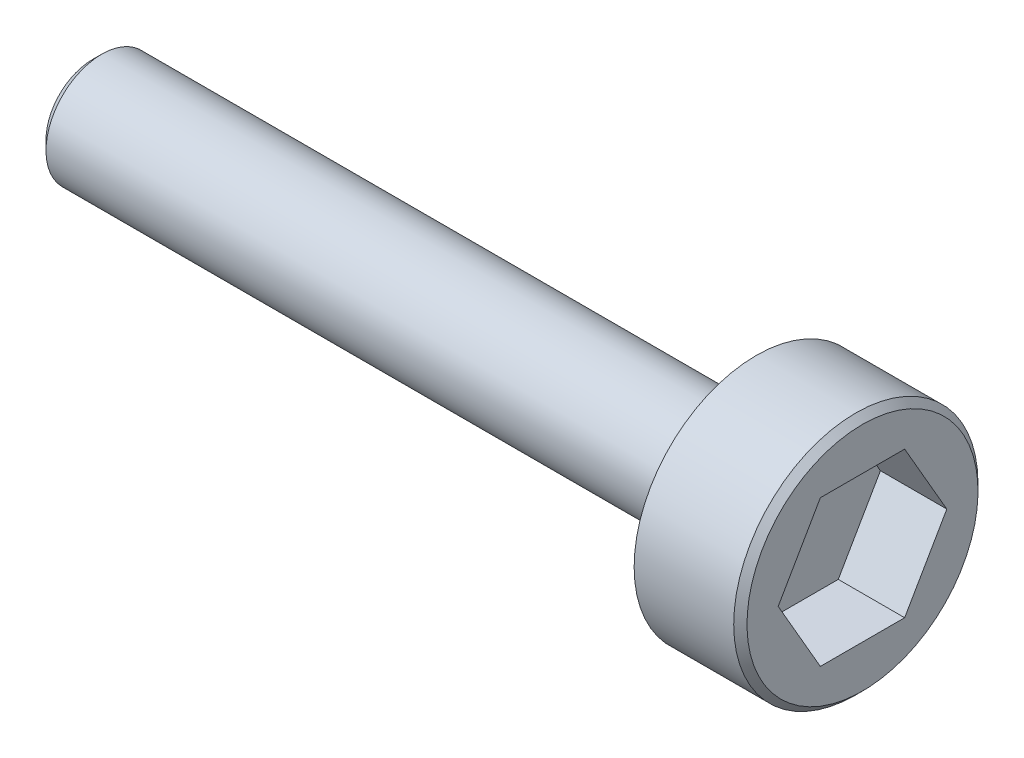
SolidWorks part; units mm, degrees
material "1023 Carbon Steel Sheet (SS)"
ref_plane "Ebene vorne" through (0, 0, 0) normal (0, 0, 1) x (1, 0, 0)
ref_plane "Ebene oben" through (0, 0, 0) normal (0, 1, 0) x (1, 0, 0)
ref_plane "Ebene rechts" through (0, 0, 0) normal (1, 0, 0) x (0, 0, -1)
sketch "Sketch1" plane through (0, 0, 0) normal (0, 0, 1) x (1, 0, 0)
  line L0 (0, 0) -> (-25, 0)
  line L1 (-25, 0) -> (-25, 1.75)
  line L2 (-25, 1.75) -> (-24.65, 2.1)
  line L3 (-24.65, 2.1) -> (0, 2.1)
  line L4 (0, 2.1) -> (0, 4.6)
  line L5 (0, 4.6) -> (3.75, 4.6)
  line L6 (4, 4.35) -> (4, 0)
  line L7 (4, 0) -> (0, 0)
  line L8 (3.75, 4.6) -> (4, 4.35)
  dimension "D1" = 2.1
  dimension "D2" = 25
  dimension "D3" = 1.75
  dimension "D4" = 135
  dimension "D5" = 4
  dimension "D6" = 3.75
  dimension "D7" = 135
  dimension "D8" = 2.5
revolve "Revolve1" add sketch "Sketch1" angle 360 about L0
sketch "Sketch2" plane through (4, 0, 0) normal (1, 0, 0) x (0, 0, -1)
  line L0 (0, 2.75) -> (-1.5877, 2.75)
  line L1 (0, 2.75) -> (1.5877, 2.75)
  line L2 (1.5877, 2.75) -> (2.3816, 1.375)
  line L3 (2.3816, 1.375) -> (3.1754, 0)
  line L4 (3.1754, 0) -> (2.3816, -1.375)
  line L5 (2.3816, -1.375) -> (1.5877, -2.75)
  line L6 (1.5877, -2.75) -> (0, -2.75)
  line L7 (0, -2.75) -> (-1.5877, -2.75)
  line L8 (-1.5877, -2.75) -> (-2.3816, -1.375)
  line L9 (-2.3816, -1.375) -> (-3.1754, 0)
  line L10 (-3.1754, 0) -> (-2.3816, 1.375)
  line L11 (-1.5877, 2.75) -> (-2.3816, 1.375)
  circle A0 centre (0, 0) radius 2.75 construction
  dimension "D1" = 5.5
extrude "Cut-Extrude1" cut sketch "Sketch2" against normal blind 2.5
